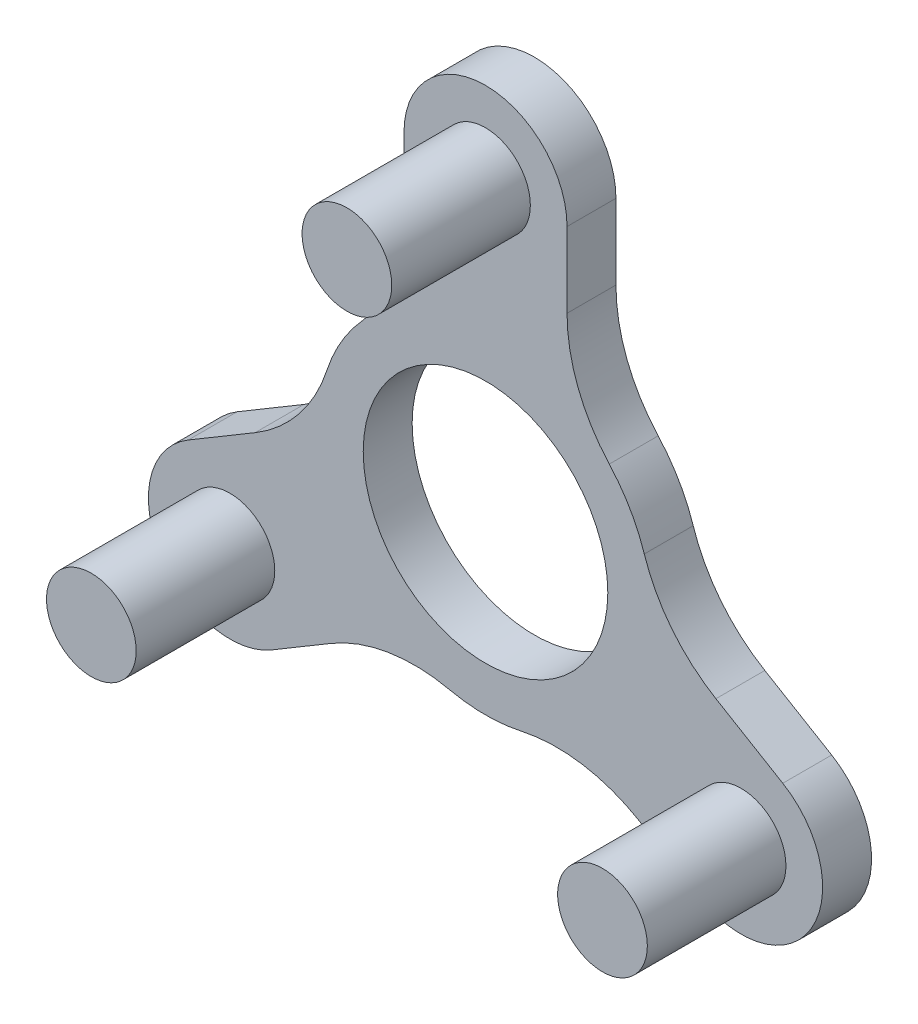
SolidWorks part; units mm, degrees
ref_plane "Alzado" through (0, 0, 0) normal (0, 0, 1) x (1, 0, 0)
ref_plane "Planta" through (0, 0, 0) normal (0, 1, 0) x (1, 0, 0)
ref_plane "Vista lateral" through (0, 0, 0) normal (1, 0, 0) x (0, 0, -1)
sketch "Croquis1" plane through (0, 0, 0) normal (0, 0, 1) x (1, 0, 0)
  line L0 (-18.2318, -4.7531) -> (-10.2435, 0)
  line L1 (-13.1183, -13.3469) -> (-5.359, -8.7299)
  line L2 (13.1183, -13.3469) -> (5.359, -8.7299)
  line L3 (-13.1183, -13.3469) -> (-18.2318, -4.7531)
  line L7 (13.1183, -13.3469) -> (18.2318, -4.7531)
  line L11 (-5, 18.2) -> (5, 18.2)
  line L15 (18.2318, -4.7531) -> (10.2435, 0)
  line L16 (-5, 18.2) -> (-5, 8.9404)
  line L17 (5, 18.2) -> (5, 8.9404)
  circle A0 centre (0, 18.2) radius 5
  circle A1 centre (15.6751, -9.05) radius 5
  circle A2 centre (-15.6751, -9.05) radius 5
  circle A3 centre (0, 0) radius 10.2435
  dimension "D7" = 10
  dimension "D8" = 10
  dimension "D9" = 10
  dimension "D1" = 90
  dimension "D2" = 90
  dimension "D3" = 90
  dimension "D4" = 18.1
  dimension "D5" = 18.1
  dimension "D6" = 18.2
  dimension "D10" = 90
  dimension "D11" = 90
  dimension "D12" = 90
extrude "Saliente-Extruir1" add sketch "Croquis1" along normal blind 3 contours L3 A2 | L3 A2 | A3 L0 A2 L1 | A3 | A3 L2 A1 L15 | A3 L17 A0 L16 | L11 A0 | L11 A0
sketch "Croquis2" plane through (0, 0, 3) normal (0, 0, 1) x (1, 0, 0)
  circle A0 centre (0, 18.2) radius 2.75
  circle A1 centre (15.6751, -9.05) radius 2.75
  circle A2 centre (-15.6751, -9.05) radius 2.75
  dimension "D1" = 5.5
  dimension "D2" = 5.5
  dimension "D3" = 5.5
sketch "Croquis3" plane through (0, 0, 3) normal (0, 0, 1) x (1, 0, 0)
  circle A0 centre (0, 0) radius 7.5
  dimension "D1" = 15
extrude "Cortar-Extruir2" cut sketch "Croquis3" against normal blind 10
fillet "Redondeo1" radius 10 6 edges at (-5.359, -8.7299, 1.5) (5.359, -8.7299, 1.5) (10.2435, 0, 1.5) (5, 8.9404, 1.5) (-5, 8.9404, 1.5) (-10.2435, 0, 1.5)
extrude "Saliente-Extruir2" add sketch "Croquis2" along normal blind 8.5
